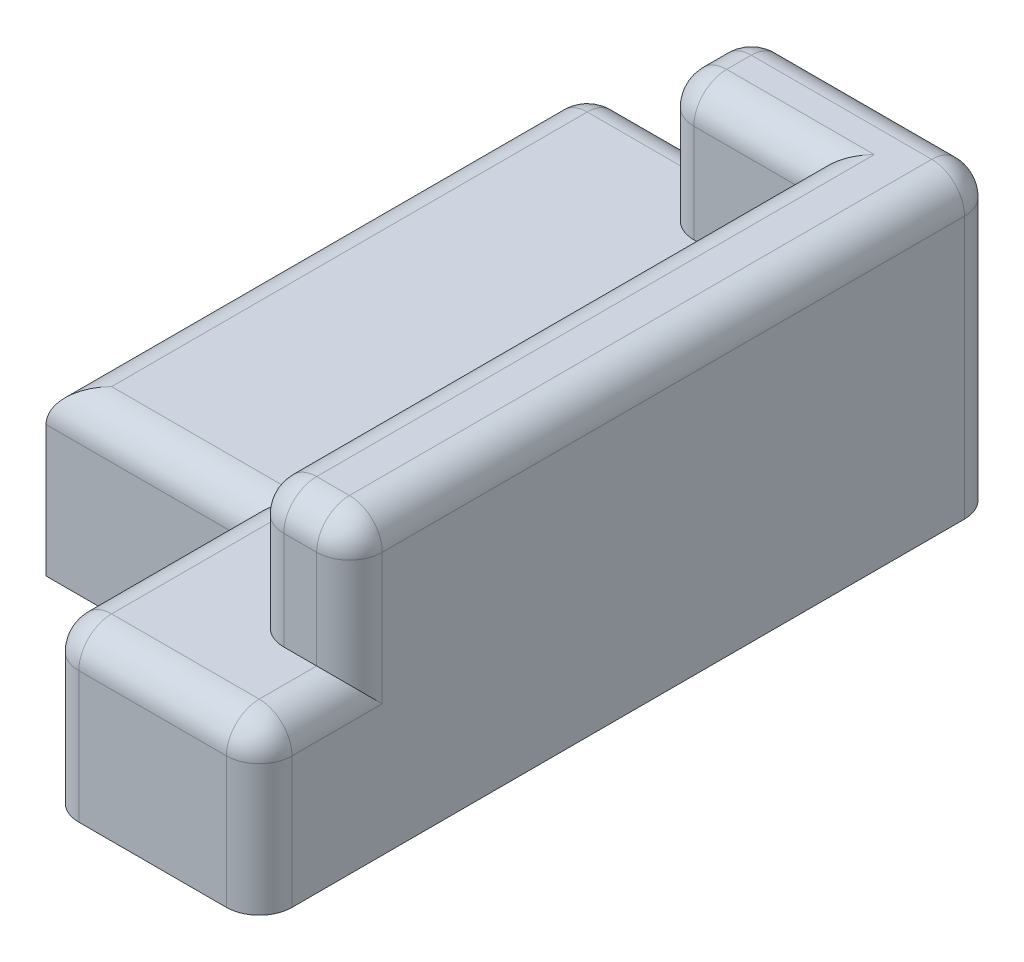
SolidWorks part; units mm, degrees
material "ABS"
ref_plane "Plano frontal" through (0, 0, 0) normal (0, 0, 1) x (1, 0, 0)
ref_plane "Plano superior" through (0, 0, 0) normal (0, 1, 0) x (1, 0, 0)
ref_plane "Plano direito" through (0, 0, 0) normal (1, 0, 0) x (0, 0, -1)
sketch "Esboço1" plane through (0, 0, 0) normal (0, 1, 0) x (1, 0, 0)
  line L1 (0, 0) -> (25, 0)
  line L2 (0, 0) -> (0, 45)
  line L3 (0, 45) -> (25, 45)
  line L4 (25, 0) -> (25, 45)
  dimension "D1" = 25
  dimension "D2" = 45
extrude "Ressalto-extrusão1" add sketch "Esboço1" along normal blind 10 contours L3 L4 L1 L2
sketch "Esboço2" plane through (0, 10, 0) normal (0, 1, 0) x (1, 0, 0)
  line L0 (0, 5.5) -> (0, 39.5) construction
  line L1 (0, 0) -> (0, 45) construction
  line L2 (0, 39.5) -> (19, 39.5)
  line L3 (25, 0) -> (25, 45) construction
  line L4 (25, 39.5) -> (25, 45)
  line L5 (25, 45) -> (0, 45)
  line L6 (0, 45) -> (0, 39.5)
  line L7 (0, 5.5) -> (0, 0)
  line L8 (0, 0) -> (25, 0)
  line L10 (19, 5.5) -> (0, 5.5)
  line L11 (19, 39.5) -> (19, 5.5)
  line L12 (25, 39.5) -> (25, 0)
  point P5 (0, 22.5)
  dimension "D1" = 34
  dimension "D2" = 5.5
  dimension "D3" = 5.5
  dimension "D4" = 6
extrude "Ressalto-extrusão2" add sketch "Esboço2" along normal blind 28
sketch "Esboço3" plane through (0, 38, 0) normal (0, 1, 0) x (1, 0, 0)
  line L1 (25, 45) -> (0, 45)
  line L2 (25, 45) -> (25, 0)
  line L3 (25, 0) -> (0, 0)
  line L4 (0, 45) -> (0, 0)
extrude "Ressalto-extrusão3" add sketch "Esboço3" along normal blind 6
sketch "Esboço4" plane through (0, 0, 0) normal (0, -1, 0) x (1, 0, 0)
  line L0 (0, -10) -> (25, -10) construction
  line L1 (0, 0) -> (0, -45) construction
  line L2 (25, 0) -> (25, -45) construction
  line L3 (0, -42) -> (25, -42) construction
  line L4 (0, -45) -> (25, -45) construction
  line L5 (0, 0) -> (25, 0) construction
  point P12 (5, -10)
  point P13 (15, -10)
  point P14 (5, -42)
  point P15 (20, -42)
  dimension "D1" = 3
  dimension "D2" = 10
  dimension "D3" = 5
  dimension "D4" = 5
  dimension "D5" = 5
  dimension "D6" = 10
hole_wizard "Furo de diâmetro Ø4.0 (4)1" positions "3DSketch1" profile "Esboço5" hole size "Ø4.0" standard "ISO"
sketch3d "3DSketch1"
  point P3 (15, 0, -10)
  point P6 (20, 0, -42)
  point P9 (5, 0, -42)
sketch "Esboço5" plane through (15, 0, -10) normal (1, 0, 0) x (0, 0, -1)
  line L0 (0, 0) -> (0, 6.2017)
  line L1 (0, 6.2017) -> (2, 5)
  line L2 (2, 5) -> (2, 0)
  line L5 (2, 0) -> (0, 0)
  line L10 (0, 6.2017) -> (-2, 5) construction
  line L11 (0, -6.35) -> (0, 107.95) construction
  dimension "Hole Dia." = 4
  dimension "Hole Depth" = 5
  dimension "Drill Angle" = 118
sketch "Esboço7" plane through (0, 0, -45) normal (0, 0, -1) x (-1, 0, 0)
  line L0 (0, 10) -> (-10, 10)
  line L1 (-10, 10) -> (-10, 38)
  line L2 (-10, 38) -> (0, 38)
  line L3 (0, 44) -> (0, 0) construction
  line L4 (0, 38) -> (0, 10)
  line L5 (0, 38) -> (-19, 38) construction
  dimension "D1" = 10
extrude "Corte-extrusão2" cut sketch "Esboço7" against normal up to surface (5.5 mm away) up to face at (9.5, 24, -39.5)
sketch "Esboço8" plane through (0, 0, 0) normal (-1, 0, 0) x (0, 0, 1)
  line L1 (0, 0) -> (-12, 0)
  line L2 (0, 0) -> (0, 12)
  line L3 (0, 12) -> (-12, 12)
  line L4 (-12, 0) -> (-12, 12)
  dimension "D1" = 12
  dimension "D2" = 12
extrude "Corte-extrusão3" cut sketch "Esboço8" against normal blind 12
sketch "Esboço9" plane through (0, 0, 0) normal (-1, 0, 0) x (0, 0, 1)
  line L0 (-45, 44) -> (-45, 18)
  line L1 (-45, 38) -> (-45, 10) construction
  line L2 (-45, 18) -> (-5.5, 18)
  line L3 (-5.5, 38) -> (-5.5, 10) construction
  line L4 (-5.5, 18) -> (-5.5, 10)
  line L5 (-5.5, 10) -> (0, 10)
  line L6 (0, 0) -> (0, 12) construction
  line L7 (0, 10) -> (0, 44)
  line L8 (0, 44) -> (-45, 44)
  dimension "D1" = 8
extrude "Corte-extrusão4" cut sketch "Esboço9" against normal through all
fillet "Filete2" radius 2 20 edges at (19, 18, -22.5) (14.5, 18, -39.5) (10, 18, -42.25) (17.5, 18, -45) (25, 18, -25.25) (22, 18, -5.5) (25, 9, -45) (25, 14, -5.5) (25, 10, -2.75) (25, 5, 0) (12, 10, -6) (18.5, 10, 0) (12, 5, 0) (6, 10, -12) (19, 14, -5.5) (10, 14, -39.5) (0, 5, -45) (0, 10, -28.5) (5, 10, -45) (10, 14, -45)
